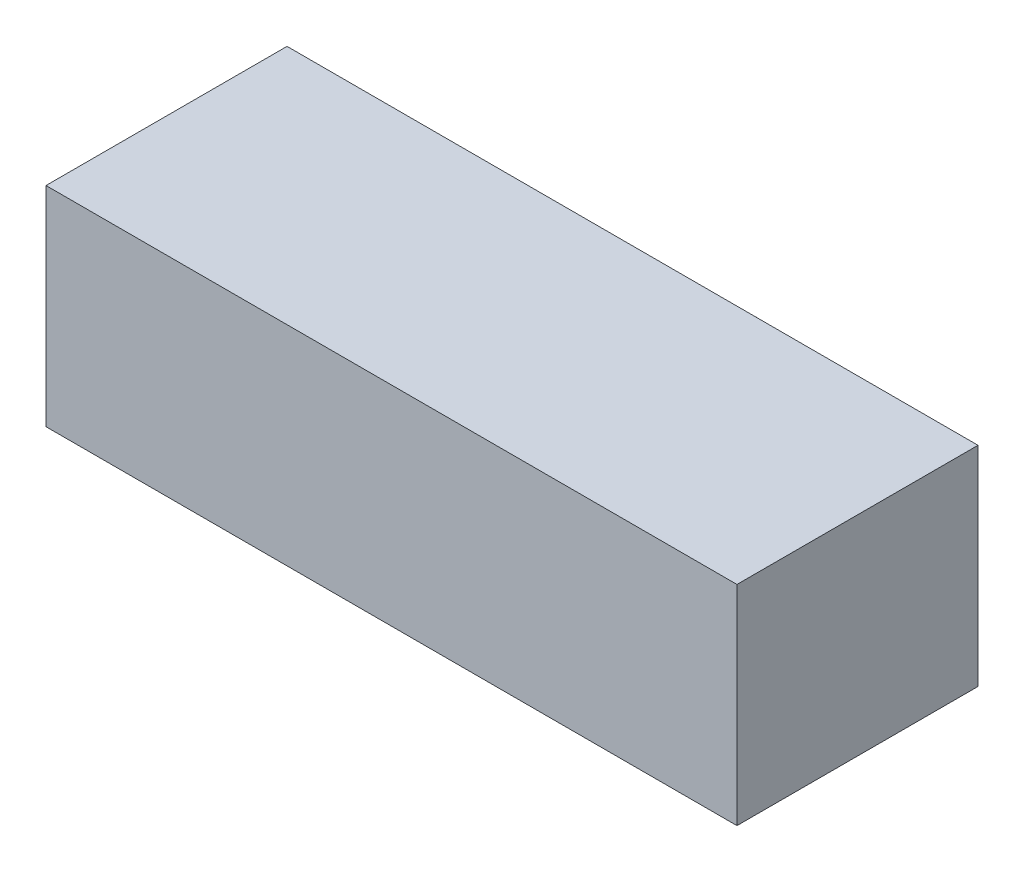
SolidWorks part; units mm, degrees
ref_plane "前视基准面" through (0, 0, 0) normal (0, 0, 1) x (1, 0, 0)
ref_plane "上视基准面" through (0, 0, 0) normal (0, 1, 0) x (1, 0, 0)
ref_plane "右视基准面" through (0, 0, 0) normal (1, 0, 0) x (0, 0, -1)
sketch "草图1" plane through (0, 0, 0) normal (0, 1, 0) x (1, 0, 0)
  line L1 (-215, -75) -> (215, -75)
  line L2 (-215, -75) -> (-215, 75)
  line L3 (-215, 75) -> (215, 75)
  line L4 (215, -75) -> (215, 75)
  line L5 (-215, -75) -> (215, 75) construction
  line L6 (-215, 75) -> (215, -75) construction
  point P0 (0, 0)
  dimension "D1" = 430
  dimension "D2" = 150
extrude "凸台-拉伸1" add sketch "草图1" along normal mid plane 130
